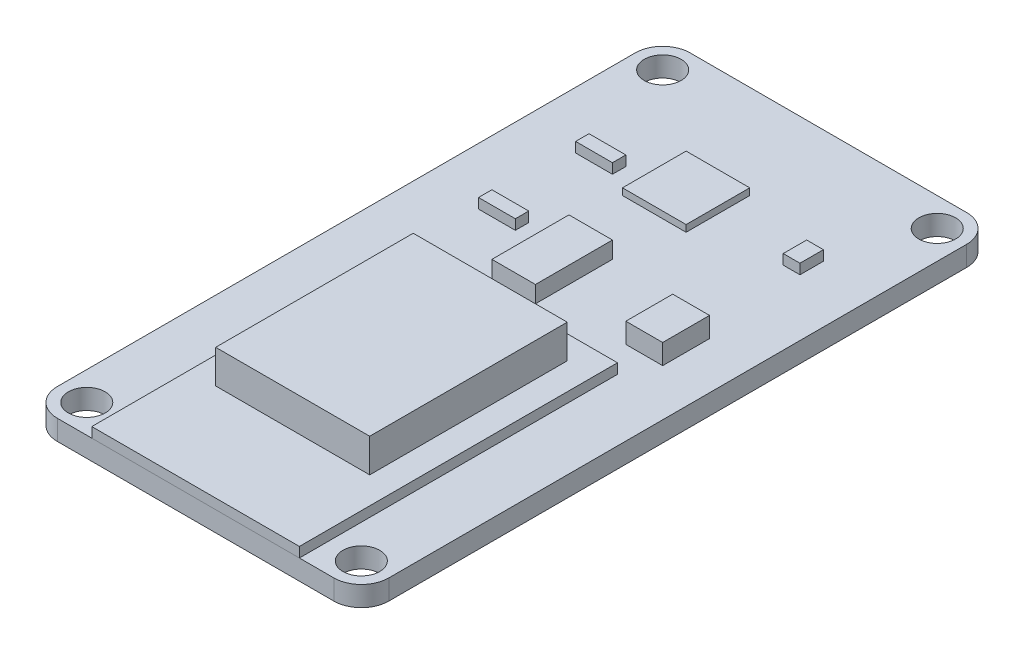
SolidWorks part; units mm, degrees
ref_plane "Front" through (0, 0, 0) normal (0, 0, 1) x (1, 0, 0)
ref_plane "Top" through (0, 0, 0) normal (0, 1, 0) x (1, 0, 0)
ref_plane "Right" through (0, 0, 0) normal (1, 0, 0) x (0, 0, -1)
sketch "Sketch1" plane through (0, 0, 0) normal (0, 1, 0) x (1, 0, 0)
  line L1 (-12.573, 24.003) -> (12.573, 24.003)
  line L2 (-12.573, 24.003) -> (-12.573, -24.003)
  line L3 (-12.573, -24.003) -> (12.573, -24.003)
  line L4 (12.573, 24.003) -> (12.573, -24.003)
  line L5 (-12.573, 24.003) -> (12.573, -24.003) construction
  line L6 (-12.573, -24.003) -> (12.573, 24.003) construction
  point P0 (0, 0)
  dimension "D1" = 48.006
  dimension "D2" = 25.146
extrude "Boss-Extrude1" add sketch "Sketch1" along normal blind 1.524
sketch "Sketch3" plane through (0, 1.524, 0) normal (0, 1, 0) x (1, 0, 0)
  line L0 (0, 0) -> (0, -11.938) construction
  line L1 (-7.874, 0.127) -> (7.874, 0.127)
  line L2 (-7.874, 0.127) -> (-7.874, -24.003)
  line L3 (-7.874, -24.003) -> (7.874, -24.003)
  line L4 (7.874, 0.127) -> (7.874, -24.003)
  line L5 (-7.874, 0.127) -> (7.874, -24.003) construction
  line L6 (-7.874, -24.003) -> (7.874, 0.127) construction
  line L7 (-12.573, -24.003) -> (12.573, -24.003) construction
  point P0 (0, -11.938)
  dimension "D1" = 24.13
  dimension "D2" = 15.748
extrude "Boss-Extrude3" add sketch "Sketch3" along normal blind 0.762 separate body
sketch "Sketch2" plane through (0, 2.286, 0) normal (0, 1, 0) x (1, 0, 0)
  line L0 (0, -9.144) -> (0, 0) construction
  line L1 (-5.842, -1.651) -> (5.842, -1.651)
  line L2 (-5.842, -1.651) -> (-5.842, -16.637)
  line L3 (-5.842, -16.637) -> (5.842, -16.637)
  line L4 (5.842, -1.651) -> (5.842, -16.637)
  line L5 (-5.842, -1.651) -> (5.842, -16.637) construction
  line L6 (-5.842, -16.637) -> (5.842, -1.651) construction
  line L7 (-12.573, -24.003) -> (12.573, -24.003) construction
  point P0 (0, -9.144)
  dimension "D1" = 7.366
  dimension "D2" = 14.986
  dimension "D3" = 11.684
extrude "Boss-Extrude2" add sketch "Sketch2" along normal blind 2.54 separate body
sketch "Sketch6" plane through (0, 1.524, 0) normal (0, 1, 0) x (1, 0, 0)
  line L0 (12.573, -24.003) -> (12.573, 24.003) construction
  line L1 (-10.414, 21.844) -> (10.414, 21.844) construction
  line L2 (-10.414, 21.844) -> (-10.414, -21.844) construction
  line L3 (-10.414, -21.844) -> (10.414, -21.844) construction
  line L4 (10.414, 21.844) -> (10.414, -21.844) construction
  line L5 (-12.573, -24.003) -> (12.573, -24.003) construction
  line L6 (0, 0) -> (0, -21.844) construction
  line L7 (0, 0) -> (10.414, 0) construction
  circle A0 centre (10.414, 21.844) radius 1.397
  circle A1 centre (-10.414, 21.844) radius 1.397
  circle A2 centre (-10.414, -21.844) radius 1.397
  circle A3 centre (10.414, -21.844) radius 1.397
  dimension "D1" = 2.794
  dimension "D2" = 0.762
  dimension "D3" = 0.762
extrude "Cut-Extrude1" cut sketch "Sketch6" against normal through all
fillet "Fillet1" radius 2.0828 4 edges at (-12.573, 0.762, -24.003) (12.573, 0.762, -24.003) (12.573, 0.762, 24.003) (-12.573, 0.762, 24.003)
sketch "Sketch7" plane through (0, 1.524, 0) normal (0, 1, 0) x (1, 0, 0)
  line L0 (-12.573, 21.9202) -> (-12.573, -21.9202) construction
  line L1 (-3.175, 7.493) -> (0.127, 7.493)
  line L2 (-3.175, 7.493) -> (-3.175, 1.651)
  line L3 (-3.175, 1.651) -> (0.127, 1.651)
  line L4 (0.127, 7.493) -> (0.127, 1.651)
  line L7 (-7.874, -24.003) -> (7.874, -24.003) construction
  dimension "D1" = 9.398
  dimension "D2" = 3.302
  dimension "D3" = 5.842
  dimension "D4" = 31.496
extrude "Boss-Extrude4" add sketch "Sketch7" along normal blind 1.27
sketch "Sketch8" plane through (0, 1.524, 0) normal (0, 1, 0) x (1, 0, 0)
  line L0 (-12.573, 21.9202) -> (-12.573, -21.9202) construction
  line L1 (-3.683, 16.891) -> (1.143, 16.891)
  line L2 (-3.683, 16.891) -> (-3.683, 12.065)
  line L3 (-3.683, 12.065) -> (1.143, 12.065)
  line L4 (1.143, 16.891) -> (1.143, 12.065)
  line L6 (10.4902, 24.003) -> (-10.4902, 24.003) construction
  line L7 (0.127, 7.493) -> (-3.175, 7.493) construction
  dimension "D1" = 4.826
  dimension "D2" = 8.89
  dimension "D3" = 11.938
  dimension "D4" = 4.572
extrude "Boss-Extrude5" add sketch "Sketch8" along normal blind 0.508
sketch "Sketch9" plane through (0, 1.524, 0) normal (0, 1, 0) x (1, 0, 0)
  line L0 (12.573, -21.9202) -> (12.573, 21.9202) construction
  line L1 (6.223, 5.969) -> (9.017, 5.969)
  line L2 (6.223, 5.969) -> (6.223, 2.413)
  line L3 (6.223, 2.413) -> (9.017, 2.413)
  line L4 (9.017, 5.969) -> (9.017, 2.413)
  line L5 (7.874, 0.127) -> (-7.874, 0.127) construction
  dimension "D1" = 2.794
  dimension "D2" = 3.556
  dimension "D3" = 3.556
  dimension "D4" = 2.286
extrude "Boss-Extrude6" add sketch "Sketch9" along normal blind 1.524
sketch "Sketch10" plane through (0, 1.524, 0) normal (0, 1, 0) x (1, 0, 0)
  line L0 (-3.175, 7.493) -> (-3.175, 1.651) construction
  line L1 (-8.255, 6.731) -> (-5.461, 6.731)
  line L2 (-8.255, 6.731) -> (-8.255, 5.715)
  line L3 (-8.255, 5.715) -> (-5.461, 5.715)
  line L4 (-5.461, 6.731) -> (-5.461, 5.715)
  line L5 (-8.255, 14.097) -> (-5.461, 14.097)
  line L6 (-8.255, 14.097) -> (-8.255, 13.081)
  line L7 (-8.255, 13.081) -> (-5.461, 13.081)
  line L8 (-5.461, 14.097) -> (-5.461, 13.081)
  line L9 (6.985, 15.367) -> (8.255, 15.367)
  line L10 (6.985, 15.367) -> (6.985, 13.589)
  line L11 (6.985, 13.589) -> (8.255, 13.589)
  line L12 (8.255, 15.367) -> (8.255, 13.589)
  line L13 (10.4902, 24.003) -> (-10.4902, 24.003) construction
  line L16 (12.573, -21.9202) -> (12.573, 21.9202) construction
  dimension "D1" = 1.27
  dimension "D2" = 1.778
  dimension "D3" = 2.794
  dimension "D4" = 1.016
  dimension "D5" = 2.286
  dimension "D6" = 8.382
  dimension "D7" = 18.288
  dimension "D8" = 5.588
  dimension "D9" = 10.414
extrude "Boss-Extrude7" add sketch "Sketch10" along normal blind 0.762
